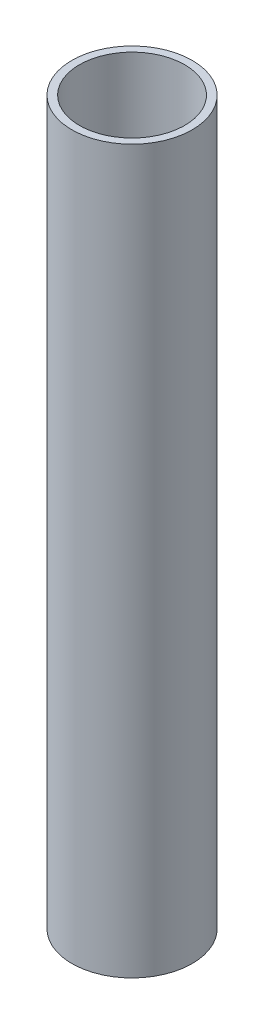
SolidWorks part; units mm, degrees
material "6061-T6 (SS)"
ref_plane "Front Plane" through (0, 0, 0) normal (0, 0, 1) x (1, 0, 0)
ref_plane "Top Plane" through (0, 0, 0) normal (0, 1, 0) x (1, 0, 0)
ref_plane "Right Plane" through (0, 0, 0) normal (1, 0, 0) x (0, 0, -1)
sketch "Sketch1" plane through (0, 0, 0) normal (0, 1, 0) x (1, 0, 0)
  circle A0 centre (0, 0) radius 25.4
  circle A1 centre (0, 0) radius 22.225
  dimension "D1" = 50.8
  dimension "D2" = 3.175
extrude "Boss-Extrude1" add sketch "Sketch1" along normal blind 304.8
equation "\"TubeThick\"=0.125"
equation "\"D2@Sketch1\"=\"TubeThick\""
